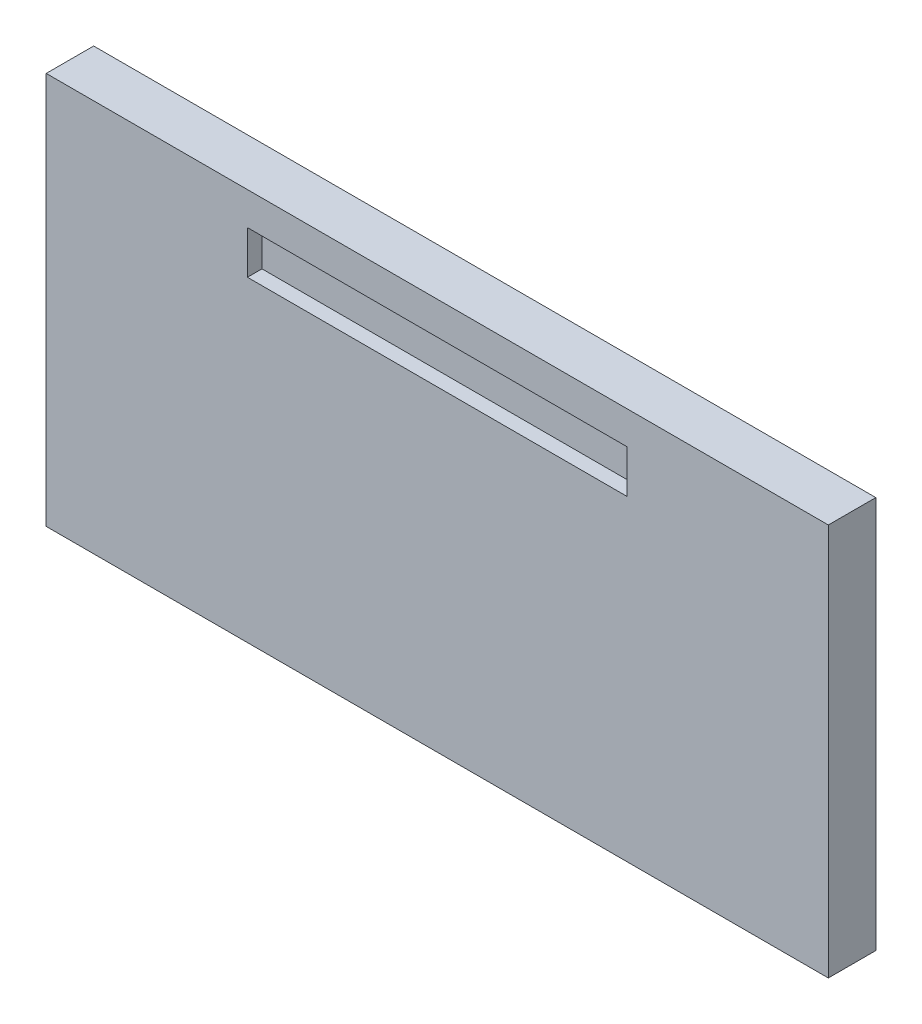
SolidWorks part; units mm, degrees
ref_plane "Front Plane" through (0, 0, 0) normal (0, 0, 1) x (1, 0, 0)
ref_plane "Top Plane" through (0, 0, 0) normal (0, 1, 0) x (1, 0, 0)
ref_plane "Right Plane" through (0, 0, 0) normal (1, 0, 0) x (0, 0, -1)
other "Configuration Table"
sketch "Sketch1" plane through (0, 0, 0) normal (0, 0, 1) x (1, 0, 0)
  line L1 (0, 0) -> (618, 0)
  line L2 (0, 0) -> (0, 310)
  line L3 (0, 310) -> (618, 310)
  line L4 (618, 0) -> (618, 310)
extrude "CEK_1L_on_pu_37.5_1" add sketch "Sketch1" along normal blind 37.5 from offset 1 separate body
sketch "Sketch2" plane through (0, 0, 0) normal (0, 0, 1) x (1, 0, 0)
  line L1 (159, 250) -> (459, 250)
  line L2 (159, 250) -> (159, 284)
  line L3 (159, 284) -> (459, 284)
  line L4 (459, 250) -> (459, 284)
extrude "CEK_1L_on_pu_37.5_2" cut sketch "Sketch2" along normal blind 14 from offset 27
